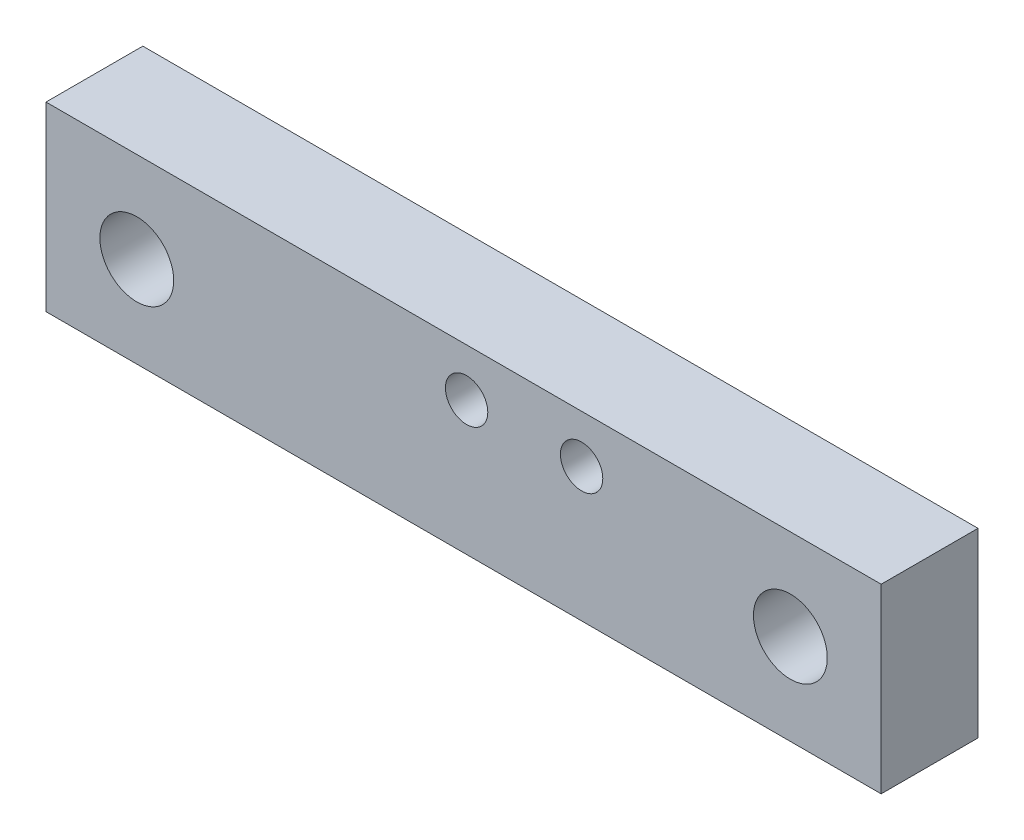
SolidWorks part; units mm, degrees
ref_plane "Front Plane" through (0, 0, 0) normal (0, 0, 1) x (1, 0, 0)
ref_plane "Top Plane" through (0, 0, 0) normal (0, 1, 0) x (1, 0, 0)
ref_plane "Right Plane" through (0, 0, 0) normal (1, 0, 0) x (0, 0, -1)
sketch "Sketch1" plane through (0, 0, 0) normal (0, 0, 1) x (1, 0, 0)
  line L1 (34.5, -7.5) -> (-34.5, -7.5)
  line L2 (34.5, -7.5) -> (34.5, 7.5)
  line L3 (34.5, 7.5) -> (-34.5, 7.5)
  line L4 (-34.5, -7.5) -> (-34.5, 7.5)
  circle A0 centre (-27, 0) radius 3.05
  circle A1 centre (27, 0) radius 3.05
  circle A2 centre (0.25, 3.55) radius 1.75
  circle A3 centre (9.75, 3.55) radius 1.75
  point P0 (0, 0)
extrude "Boss-Extrude1" add sketch "Sketch1" along normal blind 8
